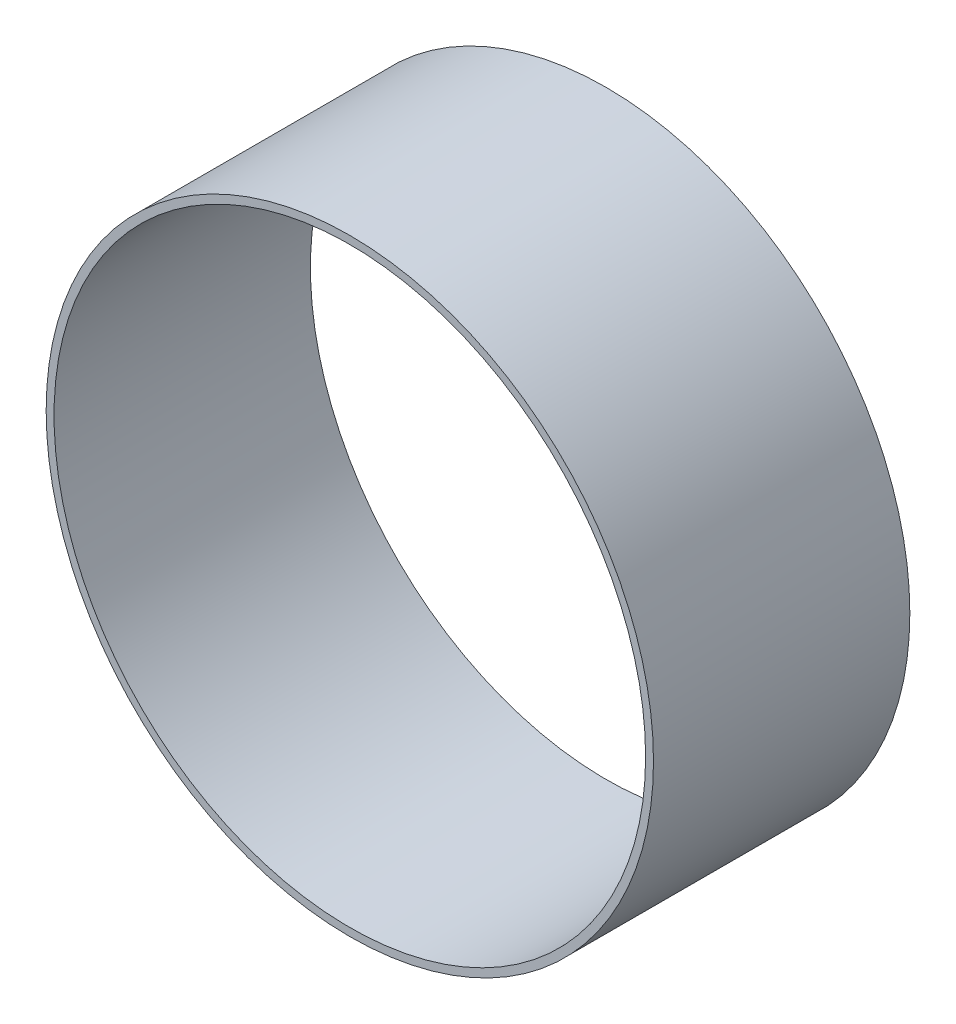
SolidWorks part; units mm, degrees
ref_plane "Спереди" through (0, 0, 0) normal (0, 0, 1) x (1, 0, 0)
ref_plane "Сверху" through (0, 0, 0) normal (0, 1, 0) x (1, 0, 0)
ref_plane "Справа" through (0, 0, 0) normal (1, 0, 0) x (0, 0, -1)
sketch "Эскиз1" plane through (0, 0, 0) normal (0, 0, 1) x (1, 0, 0)
  circle A0 centre (0, 0) radius 77
  circle A1 centre (0, 0) radius 75
extrude "Printed_fixed_case" add sketch "Эскиз1" along normal blind 65 from offset 32
